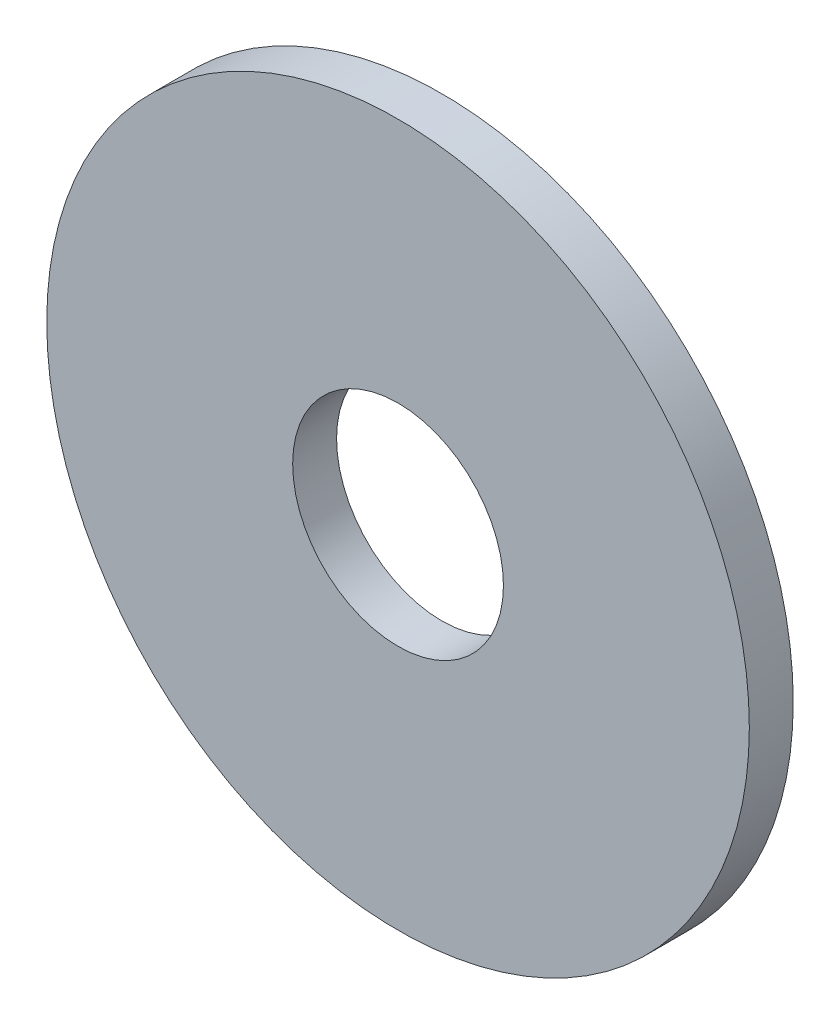
SolidWorks part; units mm, degrees
ref_plane "Front Plane" through (0, 0, 0) normal (0, 0, 1) x (1, 0, 0)
ref_plane "Top Plane" through (0, 0, 0) normal (0, 1, 0) x (1, 0, 0)
ref_plane "Right Plane" through (0, 0, 0) normal (1, 0, 0) x (0, 0, -1)
sketch "Sketch1" plane through (0, 0, 0) normal (0, 0, 1) x (1, 0, 0)
  circle A0 centre (0, 0) radius 3.81
  circle A1 centre (0, 0) radius 12.7
  dimension "D1" = 7.62
  dimension "D2" = 25.4
extrude "Boss-Extrude1" add sketch "Sketch1" along normal blind 1.5875
